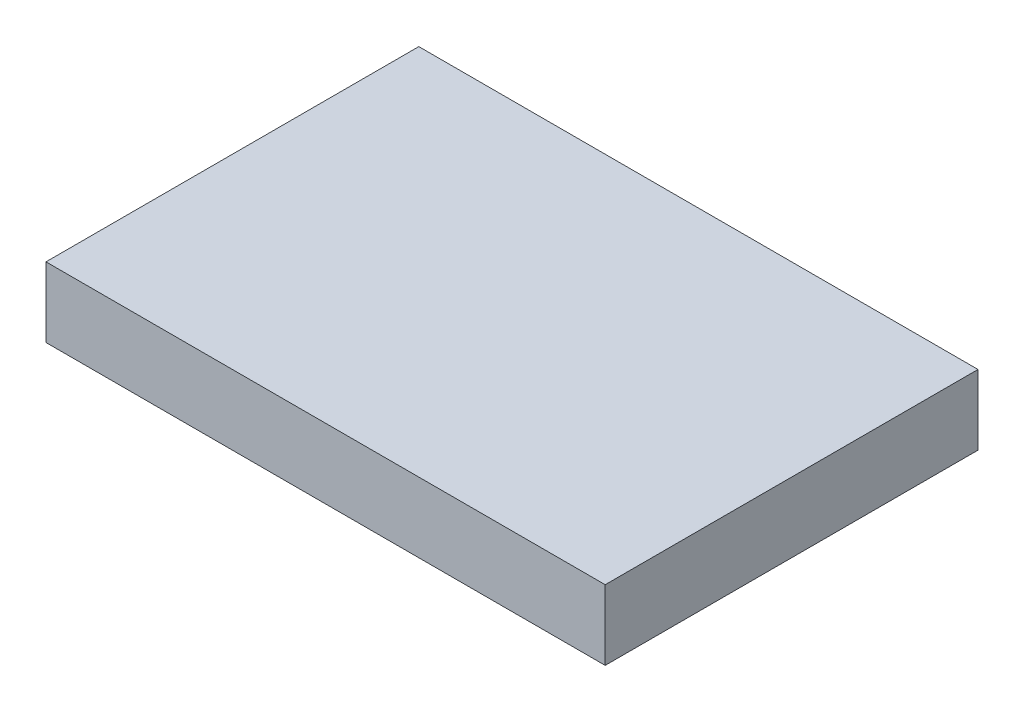
SolidWorks part; units mm, degrees
ref_plane "前视基准面" through (0, 0, 0) normal (0, 0, 1) x (1, 0, 0)
ref_plane "上视基准面" through (0, 0, 0) normal (0, 1, 0) x (1, 0, 0)
ref_plane "右视基准面" through (0, 0, 0) normal (1, 0, 0) x (0, 0, -1)
other "Configuration Table"
sketch "草图1" plane through (0, 0, 0) normal (0, 1, 0) x (1, 0, 0)
  line L1 (-60, -40) -> (60, -40)
  line L2 (-60, -40) -> (-60, 40)
  line L3 (-60, 40) -> (60, 40)
  line L4 (60, -40) -> (60, 40)
extrude "凸台-拉伸1" add sketch "草图1" against normal blind 15
sketch "草图2" plane through (0, 0, 0) normal (0, 1, 0) x (1, 0, 0)
  circle A0 centre (0, 0) radius 25
sketch "草图3" plane through (0, 0, 0) normal (0, 1, 0) x (1, 0, 0)
  circle A0 centre (40, 25) radius 5
